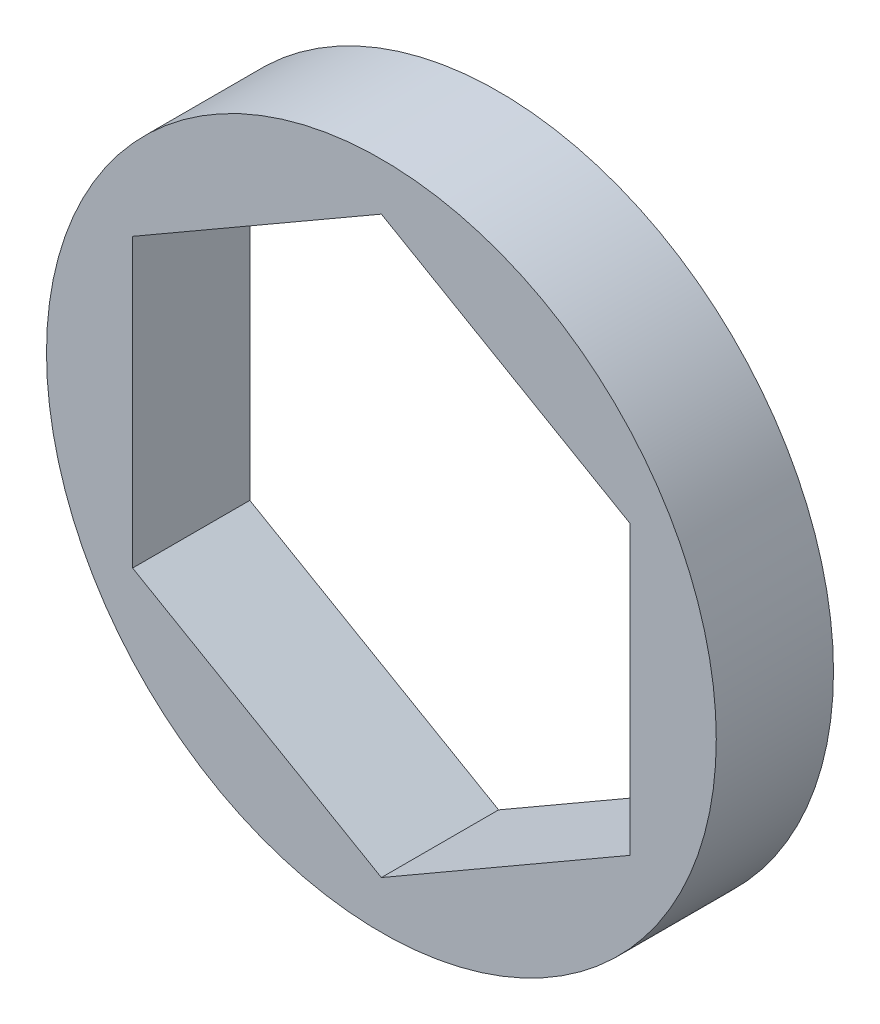
SolidWorks part; units mm, degrees
material "PET"
ref_plane "Front Plane" through (0, 0, 0) normal (0, 0, 1) x (1, 0, 0)
ref_plane "Top Plane" through (0, 0, 0) normal (0, 1, 0) x (1, 0, 0)
ref_plane "Right Plane" through (0, 0, 0) normal (1, 0, 0) x (0, 0, -1)
sketch "Sketch1" plane through (0, 0, 0) normal (0, 0, 1) x (1, 0, 0)
  line L1 (0, 7.6256) -> (-6.604, 3.8128)
  line L2 (-6.604, 3.8128) -> (-6.604, -3.8128)
  line L3 (-6.604, -3.8128) -> (0, -7.6256)
  line L4 (0, -7.6256) -> (6.604, -3.8128)
  line L5 (6.604, -3.8128) -> (6.604, 3.8128)
  line L6 (6.604, 3.8128) -> (0, 7.6256)
  circle A0 centre (0, 0) radius 8.89
  circle A1 centre (0, 0) radius 6.604 construction
  dimension "D1" = 17.78
  dimension "D2" = 13.208
extrude "Boss-Extrude1" add sketch "Sketch1" along normal mid plane 3.1115
